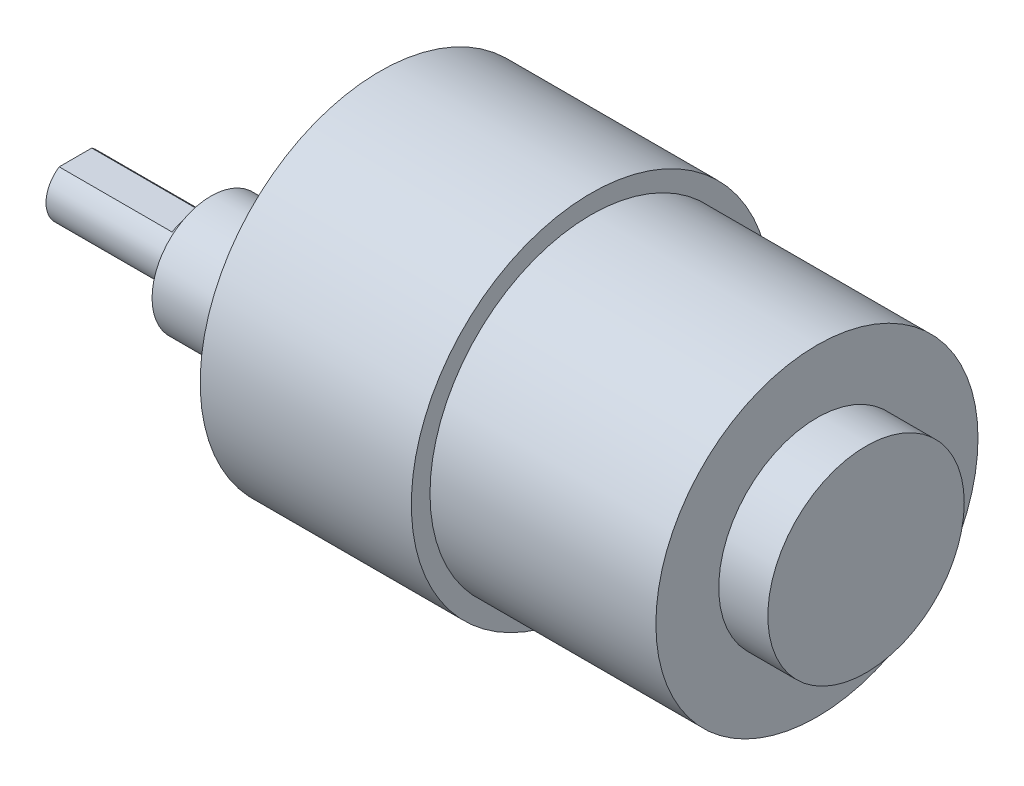
SolidWorks part; units mm, degrees
ref_plane "前视基准面" through (0, 0, 0) normal (0, 0, 1) x (1, 0, 0)
ref_plane "上视基准面" through (0, 0, 0) normal (0, 1, 0) x (1, 0, 0)
ref_plane "右视基准面" through (0, 0, 0) normal (1, 0, 0) x (0, 0, -1)
sketch "草图1" plane through (0, 0, 0) normal (1, 0, 0) x (0, 0, -1)
  circle A0 centre (0, 0) radius 3
  dimension "D1" = 6
extrude "凸台-拉伸1" add sketch "草图1" along normal blind 13.8
sketch "草图2" plane through (13.8, 0, 0) normal (1, 0, 0) x (0, 0, -1)
  circle A0 centre (0, 0) radius 6
  dimension "D1" = 12
extrude "凸台-拉伸2" add sketch "草图2" along normal blind 9.9
sketch "草图3" plane through (23.7, 0, 0) normal (1, 0, 0) x (0, 0, -1)
  circle A0 centre (0, 0) radius 18.3
  dimension "D1" = 36.6
extrude "凸台-拉伸3" add sketch "草图3" along normal blind 21.5
sketch "草图4" plane through (45.2, 0, 0) normal (1, 0, 0) x (0, 0, -1)
  circle A0 centre (0, 0) radius 16.4
  dimension "D1" = 32.8
extrude "凸台-拉伸4" add sketch "草图4" along normal blind 23
sketch "草图5" plane through (68.2, 0, 0) normal (1, 0, 0) x (0, 0, -1)
  circle A0 centre (0, 0) radius 10
  dimension "D1" = 20
extrude "凸台-拉伸5" add sketch "草图5" along normal blind 5
sketch "草图6" plane through (0, 0, 0) normal (-1, 0, 0) x (0, 0, 1)
  line L0 (-1.6583, 2.5) -> (1.6583, 2.5)
  line L1 (-1.6583, 2.5) -> (-2.4537, 4.0332)
  line L2 (-2.4537, 4.0332) -> (1.9148, 4.0332)
  line L3 (1.9148, 4.0332) -> (1.6583, 2.5)
  circle A0 centre (0, 0) radius 3 construction
  circle A1 centre (0, 0) radius 3 construction
  dimension "D1" = 2.5
extrude "切除-拉伸1" cut sketch "草图6" against normal blind 11.5
sketch "草图7" plane through (23.7, 0, 0) normal (-1, 0, 0) x (0, 0, 1)
  circle A0 centre (0, 0) radius 15.5 construction
  circle A1 centre (0, 15.5) radius 1.5
  dimension "D1" = 31
  dimension "D2" = 3
extrude "切除-拉伸2" cut sketch "草图7" against normal blind 5
pattern_circular "阵列(圆周)1" count 6 over 360 about axis through (0, 0, 0) along (1, 0, 0) of "切除-拉伸2"
sketch "草图8" plane through (0, 0, 0) normal (-1, 0, 0) x (0, 0, 1)
  circle A0 centre (0, 0) radius 8.9633
extrude "切除-拉伸3" cut sketch "草图8" against normal up to surface (23.7 mm away) up to face at (23.7, 9.049, -12.6734)
sketch "草图9" plane through (23.7, 0, 0) normal (-1, 0, 0) x (0, 0, 1)
  circle A0 centre (7.3, 0) radius 6
  point P2 (0, 15.5)
  point P5 (7.3, 0)
  dimension "D2" = 12
  dimension "D1" = 7.3
extrude "凸台-拉伸6" add sketch "草图9" along normal blind 9.9
sketch "草图10" plane through (13.8, 0, 0) normal (-1, 0, 0) x (0, 0, 1)
  circle A0 centre (7.3, 0) radius 3
  dimension "D1" = 6
extrude "凸台-拉伸7" add sketch "草图10" along normal blind 13.8
sketch "草图11" plane through (0, 0, 0) normal (-1, 0, 0) x (0, 0, 1)
  line L0 (5.6417, 2.5) -> (8.9583, 2.5)
  line L1 (5.6417, 2.5) -> (5.6417, 3.7988)
  line L2 (5.6417, 3.7988) -> (9.9361, 4.485)
  line L3 (9.9361, 4.485) -> (8.9583, 2.5)
  circle A0 centre (7.3, 0) radius 3 construction
  circle A1 centre (7.3, 0) radius 3 construction
  dimension "D1" = 2.5
extrude "切除-拉伸4" cut sketch "草图11" against normal blind 11.5
